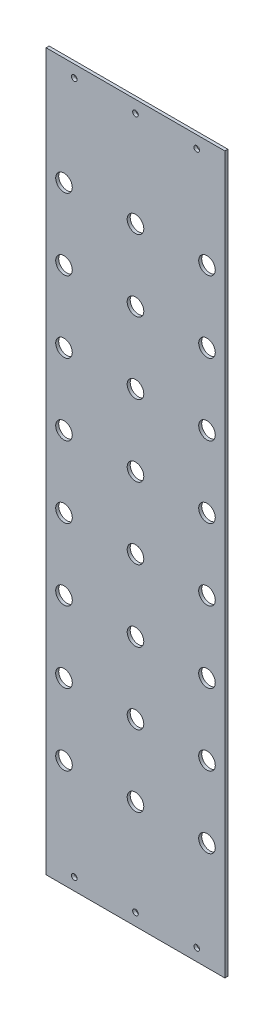
SolidWorks part; units mm, degrees
ref_plane "Front Plane" through (0, 0, 0) normal (0, 0, 1) x (1, 0, 0)
ref_plane "Top Plane" through (0, 0, 0) normal (0, 1, 0) x (1, 0, 0)
ref_plane "Right Plane" through (0, 0, 0) normal (1, 0, 0) x (0, 0, -1)
sketch "Sketch1" plane through (0, 0, 0) normal (0, 0, 1) x (1, 0, 0)
  line L1 (0, 0) -> (280.02, 0)
  line L2 (0, 0) -> (0, 1122)
  line L3 (0, 1122) -> (280.02, 1122)
  line L4 (280.02, 0) -> (280.02, 1122)
extrude "Plate" add sketch "Sketch1" along normal blind 4.76
sketch "Sketch2" plane through (0, 0, 0) normal (0, 0, 1) x (1, 0, 0)
  circle A0 centre (44.06, 19.05) radius 4.37
  circle A1 centre (44.06, 1102.95) radius 4.37
  circle A2 centre (140.01, 19.05) radius 4.37
  circle A3 centre (140.01, 1102.95) radius 4.37
  circle A4 centre (235.96, 19.05) radius 4.37
  circle A5 centre (235.96, 1102.95) radius 4.37
  circle A6 centre (28.01, 169) radius 13
  circle A7 centre (28.01, 281) radius 13
  circle A8 centre (28.01, 393) radius 13
  circle A9 centre (28.01, 505) radius 13
  circle A10 centre (28.01, 617) radius 13
  circle A11 centre (28.01, 729) radius 13
  circle A12 centre (28.01, 841) radius 13
  circle A13 centre (28.01, 953) radius 13
  circle A14 centre (140.01, 169) radius 13
  circle A15 centre (140.01, 281) radius 13
  circle A16 centre (140.01, 393) radius 13
  circle A17 centre (140.01, 505) radius 13
  circle A18 centre (140.01, 617) radius 13
  circle A19 centre (140.01, 729) radius 13
  circle A20 centre (140.01, 841) radius 13
  circle A21 centre (140.01, 953) radius 13
  circle A22 centre (252.01, 169) radius 13
  circle A23 centre (252.01, 281) radius 13
  circle A24 centre (252.01, 393) radius 13
  circle A25 centre (252.01, 505) radius 13
  circle A26 centre (252.01, 617) radius 13
  circle A27 centre (252.01, 729) radius 13
  circle A28 centre (252.01, 841) radius 13
  circle A29 centre (252.01, 953) radius 13
extrude "Holes" cut sketch "Sketch2" against normal through all and the other way through all
